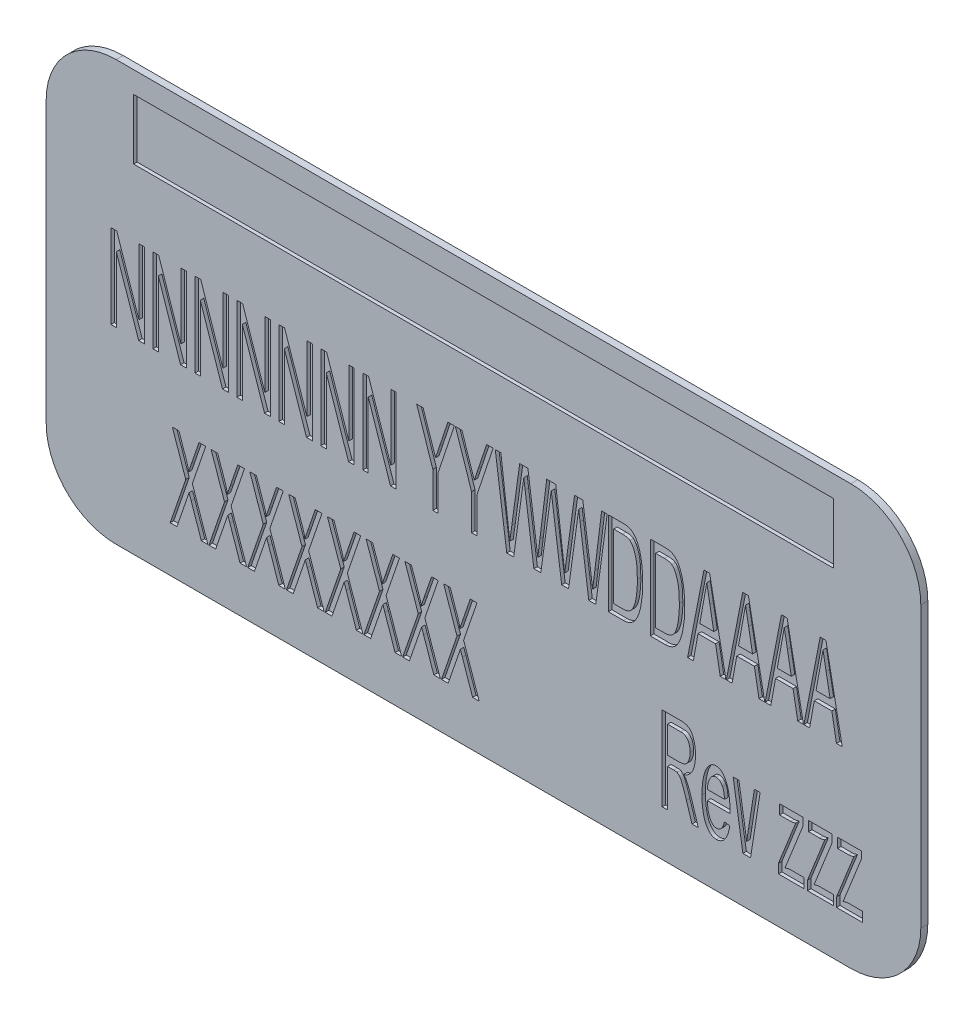
SolidWorks part; units mm, degrees
ref_plane "Face" through (0, 0, 0) normal (0, 0, 1) x (1, 0, 0)
ref_plane "Dessus" through (0, 0, 0) normal (0, 1, 0) x (1, 0, 0)
ref_plane "Droite" through (0, 0, 0) normal (1, 0, 0) x (0, 0, -1)
sketch "Esquisse1" plane through (0, 0, 0) normal (0, 0, 1) x (1, 0, 0)
  line L1 (-21.8488, 2.3382) -> (-0.8488, 2.3382)
  line L2 (-23.8488, 0.3382) -> (-23.8488, -7.6618)
  line L3 (-21.8488, -9.6618) -> (-0.8488, -9.6618)
  line L4 (1.1512, 0.3382) -> (1.1512, -7.6618)
  arc A0 (-0.8488, 2.3382) -> (1.1512, 0.3382) centre (-0.8488, 0.3382) cw
  arc A1 (1.1512, -7.6618) -> (-0.8488, -9.6618) centre (-0.8488, -7.6618) cw
  arc A2 (-21.8488, -9.6618) -> (-23.8488, -7.6618) centre (-21.8488, -7.6618) cw
  arc A3 (-23.8488, 0.3382) -> (-21.8488, 2.3382) centre (-21.8488, 0.3382) cw
  dimension "D3" = 2
  dimension "D1" = 25
  dimension "D2" = 12
extrude "Boss.-Extru.1" add sketch "Esquisse1" along normal blind 0.2
sketch "Esquisse2" plane through (0, 0, 0.2) normal (0, 0, 1) x (1, 0, 0)
  text T0 "NNNNNNN YYWWDDAAAA" font "Arial" height 2.4
extrude "Enlèv. mat.-Extru.1" cut sketch "Esquisse2" against normal blind 0.1
sketch "Esquisse8" plane through (0, 0, 0.2) normal (0, 0, 1) x (1, 0, 0)
  line L0 (-20.3043, -8.3563) -> (-1.1547, -8.3563) construction
  text T0 "XXXXXXXX           Rev zzz" font "Arial" height 2.4
extrude "Enlèv. mat.-Extru.2" cut sketch "Esquisse8" against normal blind 0.1
sketch "Esquisse10" plane through (0, 0, 0.2) normal (0, 0, 1) x (1, 0, 0)
  line L3 (-21.3488, 1.7251) -> (-1.3488, 1.7251)
  line L4 (-21.3488, 1.7251) -> (-21.3488, 0)
  line L5 (-21.3488, 0) -> (-1.3488, 0)
  line L6 (-1.3488, 1.7251) -> (-1.3488, 0)
extrude "Enlèv. mat.-Extru.3" cut sketch "Esquisse10" against normal blind 0.1
sketch "Esquisse11"
